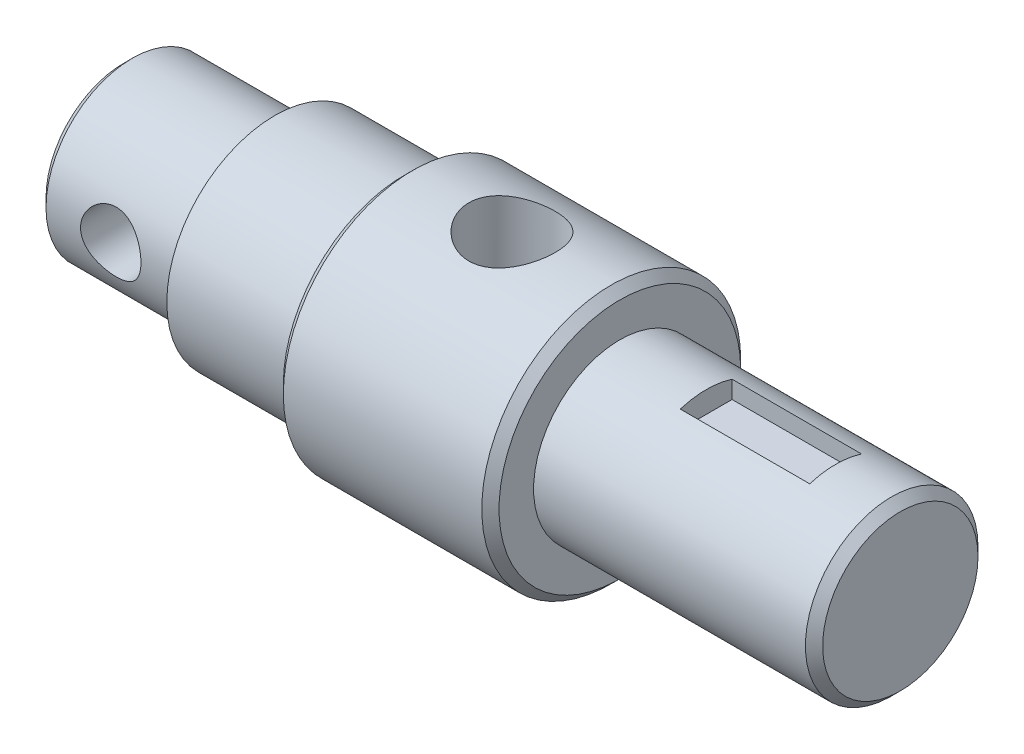
SolidWorks part; units mm, degrees
ref_plane "Спереди" through (0, 0, 0) normal (0, 0, 1) x (1, 0, 0)
ref_plane "Сверху" through (0, 0, 0) normal (0, 1, 0) x (1, 0, 0)
ref_plane "Справа" through (0, 0, 0) normal (1, 0, 0) x (0, 0, -1)
sketch "Эскиз1" plane through (0, 0, 0) normal (0, 0, 1) x (1, 0, 0)
  line L0 (0, 0) -> (-42.8669, 0) construction
  line L1 (0, 0) -> (0, 20)
  line L2 (0, 20) -> (35, 20)
  line L3 (35, 20) -> (35, 25)
  line L4 (35, 25) -> (65, 25)
  line L5 (65, 25) -> (65, 30)
  line L6 (65, 30) -> (115, 30)
  line L7 (115, 30) -> (115, 20)
  line L8 (115, 20) -> (180, 20)
  line L9 (180, 20) -> (180, 0)
  line L10 (180, 0) -> (0, 0)
  dimension "D1" = 40
  dimension "D2" = 50
  dimension "D3" = 60
  dimension "D4" = 180
  dimension "D5" = 35
  dimension "D6" = 65
  dimension "D7" = 50
revolve "Повернуть1" add sketch "Эскиз1" angle 360 about L0
sketch "Эскиз2" plane through (0, 0, 0) normal (0, 0, 1) x (1, 0, 0)
  line L0 (180, 20) -> (115, 20) construction
  line L1 (135, 20) -> (165, 20)
  line L2 (135, 20) -> (135, 15)
  line L3 (135, 15) -> (165, 15)
  line L4 (165, 20) -> (165, 15)
  line L5 (180, -20) -> (180, 20) construction
  dimension "D1" = 30
  dimension "D2" = 15
  dimension "D3" = 5
extrude "Вырез-Вытянуть1" cut sketch "Эскиз2" against normal mid plane 12
sketch "Эскиз3" plane through (0, 0, 0) normal (0, 0, 1) x (1, 0, 0)
  line L0 (0, 0) -> (35, 0) construction
  line L1 (35, 20) -> (35, -20) construction
  line L2 (0, 20) -> (0, -20) construction
  circle A0 centre (17, 0) radius 7
  dimension "D1" = 14
  dimension "D2" = 17
extrude "Вырез-Вытянуть2" cut sketch "Эскиз3" against normal through all both and the other way through all
ref_plane "Плоскость4" through (0, 30, 0) normal (0, 1, 0) x (1, 0, 0)
hole_wizard "Диаметр отверстия Ø16.0 (20)1" positions "Эскиз5" profile "Эскиз4" hole size "Ø16.0" standard "ISO"
sketch "Эскиз5" plane through (0, 30, 0) normal (0, 1, 0) x (1, 0, 0)
  line L0 (65, 30) -> (65, -30) construction
  line L1 (65, 0) -> (115, 0) construction
  line L2 (115, -20) -> (115, 20) construction
  point P0 (90, 0)
  dimension "D1" = 25
sketch "Эскиз4" plane through (90, 30, 0) normal (1, 0, 0) x (0, 0, 1)
  line L0 (0, 0) -> (0, 26.0086)
  line L1 (0, 26.0086) -> (10, 20)
  line L2 (10, 20) -> (10, 0)
  line L5 (10, 0) -> (0, 0)
  line L10 (0, 26.0086) -> (-10, 20) construction
  line L11 (0, -6.35) -> (0, 107.95) construction
  dimension "Диаметр отверстия" = 20
  dimension "Глубина отверстия" = 20
  dimension "Угол заточки сверла" = 118
pattern_circular "Круговой массив1" count 2 over 360 about axis through (0, 0, 0) along (1, 0, 0) of "Диаметр отверстия Ø16.0 (20)1"
chamfer "Фаска1" distance 2 angle 45 4 edges at (180, 0, -20) (115, 0, -30) (65, 0, -30) (0, 0, -20)
